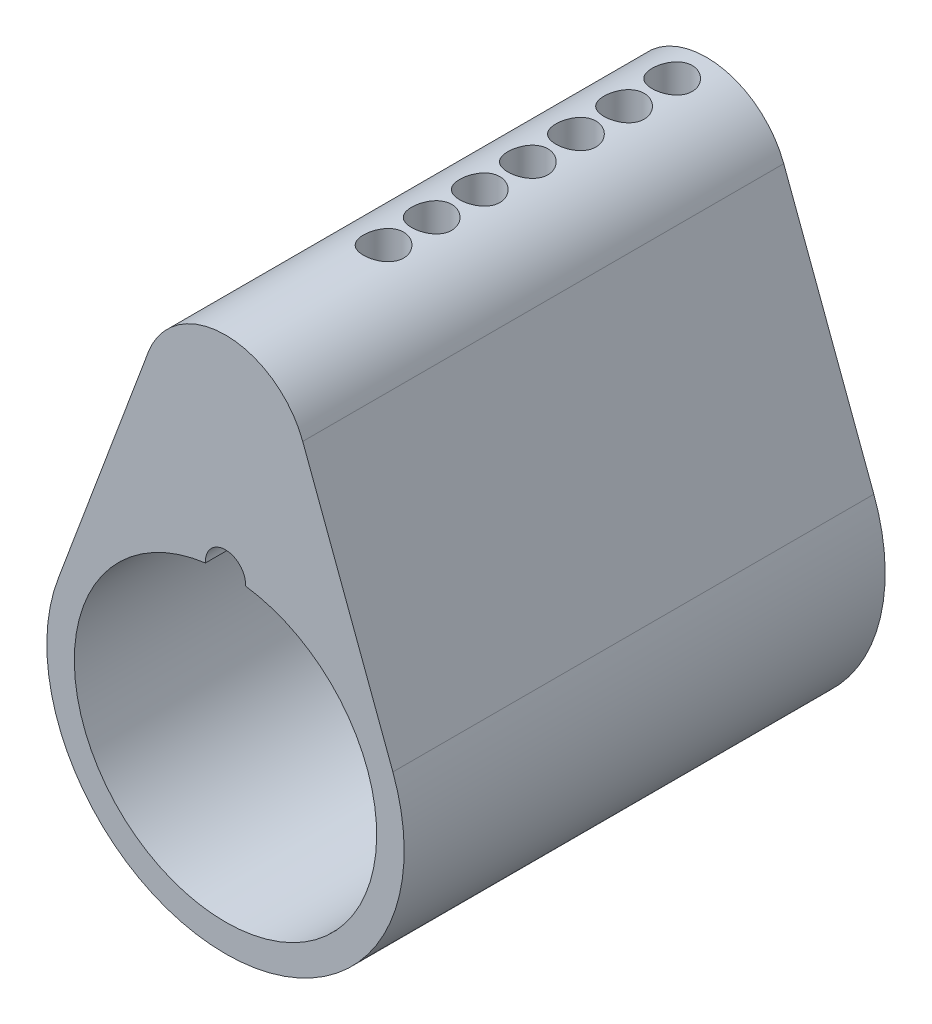
SolidWorks part; units mm, degrees
material "Brass"
ref_plane "Front Plane" through (0, 0, 0) normal (0, 0, 1) x (1, 0, 0)
ref_plane "Top Plane" through (0, 0, 0) normal (0, 1, 0) x (1, 0, 0)
ref_plane "Right Plane" through (0, 0, 0) normal (1, 0, 0) x (0, 0, -1)
sketch "Sketch1" plane through (0, 0, 0) normal (0, 0, 1) x (1, 0, 0)
  line L0 (0, -5) -> (0, -35) construction
  line L5 (0, -20) -> (0, 0) construction
  line L10 (0, 0) -> (0, -20) construction
  line L11 (-12.1777, -15.45) -> (-5.6205, 2.1)
  line L15 (5.6205, 2.1) -> (12.1777, -15.45)
  line L18 (0, -20) -> (0, -40) construction
  arc A4 (-12.1777, -15.45) -> (12.1777, -15.45) centre (0, -20) ccw
  arc A6 (5.6205, 2.1) -> (-5.6205, 2.1) centre (0, 0) ccw
  dimension "D1" = 6
  dimension "D2" = 13
  dimension "D3" = 20
extrude "Boss-Extrude2" add sketch "Sketch1" against normal up to surface (35 mm away)
sketch "Sketch2" plane through (0, 0, 0) normal (0, 0, 1) x (1, 0, 0)
  circle A0 centre (0, -20) radius 11
  circle A1 centre (0, -20) radius 11 construction
extrude "Cut-Extrude1" cut sketch "Sketch2" against normal up to surface (35 mm away) up to face at (0, -10.0875, -35)
sketch "Sketch3" plane through (0, 0, 0) normal (0, 0, 1) x (1, 0, 0)
  circle A0 centre (0, -9) radius 1.4605
  arc A1 (9.5395, -20) -> (10.903, -21.4573) centre (11, -20) ccw construction
extrude "Cut-Extrude2" cut sketch "Sketch3" against normal up to vertex (4.064 mm away)
ref_plane "Plane1" through (0, 6, 0) normal (0, 1, 0) x (1, 0, 0)
sketch "Sketch4" plane through (0, 6, 0) normal (0, 1, 0) x (1, 0, 0)
  line L0 (0, -19.25) -> (0, 19.25) construction
  line L1 (0, 32.5) -> (0, 29) construction
  line L2 (0, 33.9605) -> (0, 35) construction
  line L4 (5.6205, 35) -> (-5.6205, 35) construction
  circle A0 centre (0, 32.5) radius 1.4605
  dimension "D2" = 2.921
  dimension "D1" = 1.0395
  dimension "D3" = 3.5
extrude "Cut-Extrude3" cut sketch "Sketch4" against normal up to surface (15 mm away)
pattern_linear "LPattern1" count 7 spacing 3.5 along (0, 0, 1) of "Cut-Extrude3"
